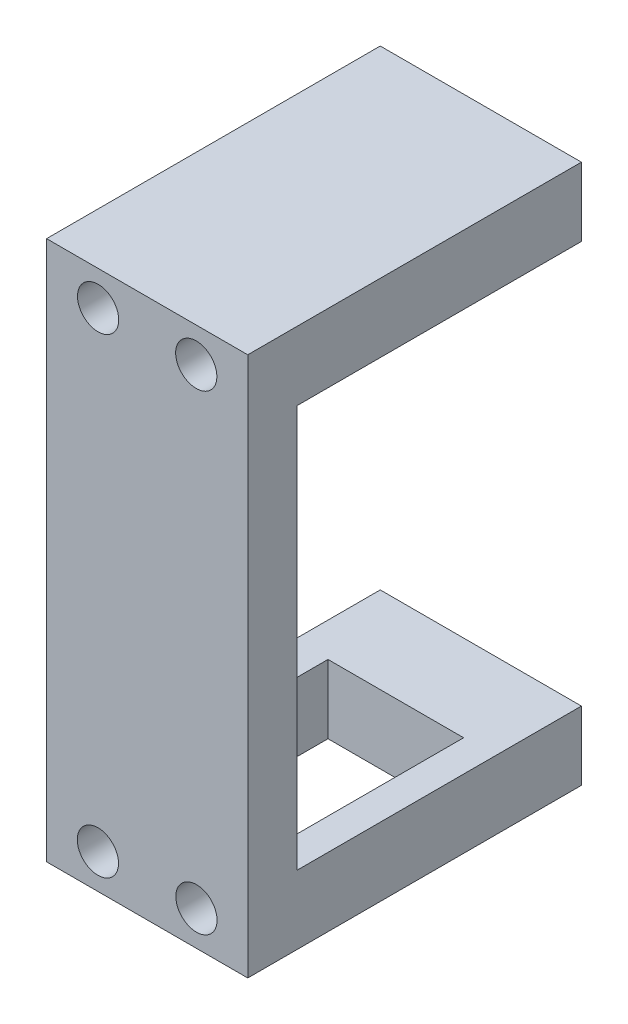
SolidWorks part; units mm, degrees
ref_plane "Front Plane" through (0, 0, 0) normal (0, 0, 1) x (1, 0, 0)
ref_plane "Top Plane" through (0, 0, 0) normal (0, 1, 0) x (1, 0, 0)
ref_plane "Right Plane" through (0, 0, 0) normal (1, 0, 0) x (0, 0, -1)
sketch "Sketch1" plane through (0, 0, 0) normal (1, 0, 0) x (0, 0, -1)
  line L1 (-2.5, 27.5) -> (2.5, 27.5)
  line L2 (-2.5, 27.5) -> (-2.5, -27.5)
  line L3 (-2.5, -27.5) -> (2.5, -27.5)
  line L4 (2.5, 20.5) -> (2.5, -20.5)
  line L5 (-2.5, 27.5) -> (2.5, -27.5) construction
  line L6 (-2.5, -27.5) -> (2.5, 27.5) construction
  line L7 (2.5, 27.5) -> (31.5, 27.5)
  line L9 (2.5, 20.5) -> (31.5, 20.5)
  line L10 (31.5, 27.5) -> (31.5, 20.5)
  line L11 (2.5, -27.5) -> (31.5, -27.5)
  line L13 (2.5, -20.5) -> (31.5, -20.5)
  line L14 (31.5, -27.5) -> (31.5, -20.5)
  point P0 (0, 0)
  dimension "D1" = 55
  dimension "D2" = 7
  dimension "D3" = 7
  dimension "D4" = 29
  dimension "D5" = 29
  dimension "D6" = 5
extrude "Boss-Extrude1" add sketch "Sketch1" along normal blind 20.5
sketch "Sketch3" plane through (0, -27.5, 0) normal (0, -1, 0) x (1, 0, 0)
  line L1 (3.4751, -22.7007) -> (17.2959, -22.7007)
  line L2 (3.4751, -22.7007) -> (3.4751, -3.1211)
  line L3 (3.4751, -3.1211) -> (17.2959, -3.1211)
  line L4 (17.2959, -22.7007) -> (17.2959, -3.1211)
  line L5 (3.4751, -22.7007) -> (17.2959, -3.1211) construction
  line L6 (3.4751, -3.1211) -> (17.2959, -22.7007) construction
  point P0 (10.3855, -12.9109)
extrude "Cut-Extrude1" cut sketch "Sketch3" against normal up to surface (7 mm away) up to face at (10.25, -20.5, -17)
sketch "Sketch4" plane through (0, 0, -31.5) normal (0, 0, -1) x (-1, 0, 0)
  line L0 (-10.25, -27.5) -> (-10.25, 29.101) construction
  line L1 (-20.5, -27.5) -> (0, -27.5) construction
  line L2 (-10.25, 29.101) -> (-10.25, 0.8005) construction
  line L3 (-10.25, 0.8005) -> (-32.885, 0.8005) construction
  circle A0 centre (-15.2714, -23.9704) radius 2.1
  circle A1 centre (-5.2286, -23.9704) radius 2.1
  circle A2 centre (-5.25, 24) radius 2.1
  circle A3 centre (-15.25, 24) radius 2.1
extrude "Cut-Extrude2" cut sketch "Sketch4" against normal blind 5
ref_plane "Plane1" through (0, 0, -14.5) normal (0, 0, 1) x (1, 0, 0)
mirror "Mirror1" about plane through (0, 0, -14.5) normal (0, 0, 1) of "Cut-Extrude2"
